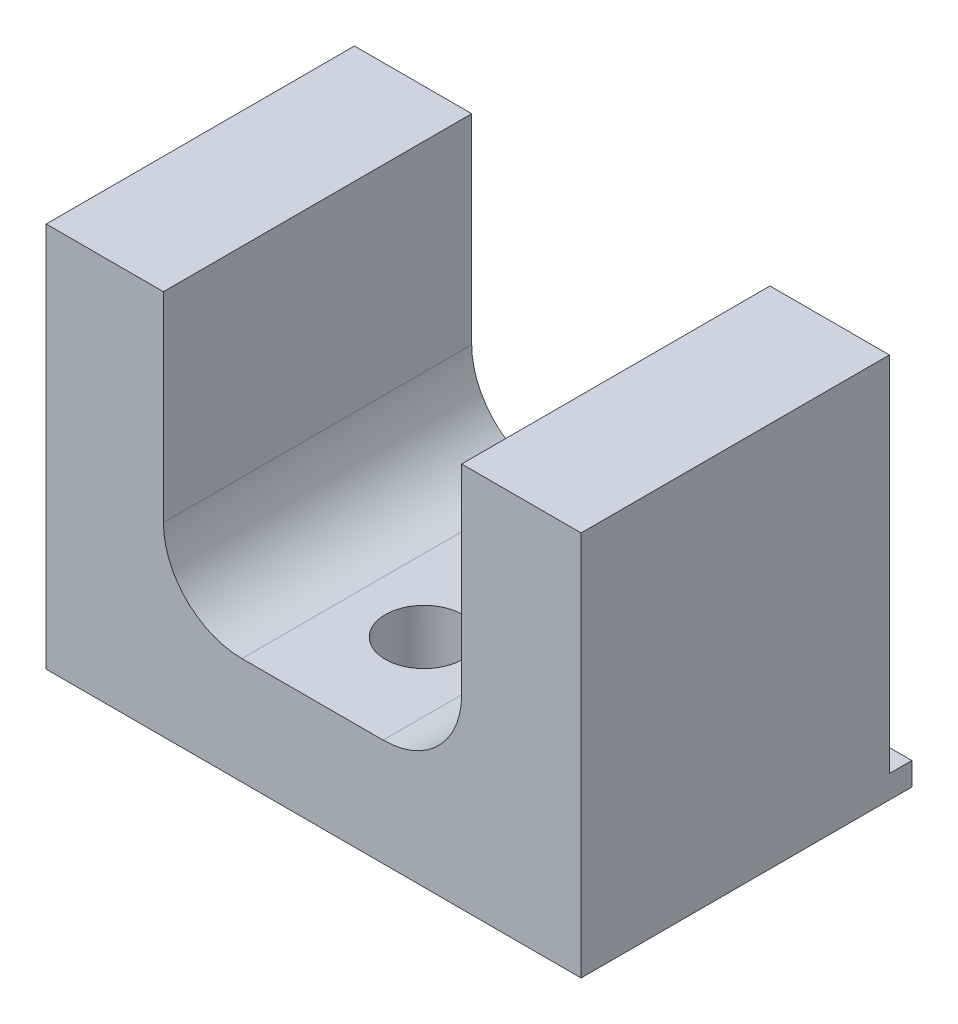
SolidWorks part; units mm, degrees
ref_plane "Front Plane" through (0, 0, 0) normal (0, 0, 1) x (1, 0, 0)
ref_plane "Top Plane" through (0, 0, 0) normal (0, 1, 0) x (1, 0, 0)
ref_plane "Right Plane" through (0, 0, 0) normal (1, 0, 0) x (0, 0, -1)
sketch "Sketch1" plane through (0, 0, 0) normal (0, 0, 1) x (1, 0, 0)
  line L0 (0, 0) -> (72.96, 0)
  line L8 (0, 0) -> (0, 52.58)
  line L9 (0, 52.58) -> (15.99, 52.58)
  line L10 (15.99, 52.58) -> (15.99, 25.31)
  line L11 (26.7, 14.6) -> (45.96, 14.6)
  line L12 (56.67, 25.31) -> (56.67, 52.57)
  line L13 (56.67, 52.57) -> (72.96, 52.57)
  line L14 (72.96, 52.57) -> (72.96, 0)
  arc A0 (45.96, 14.6) -> (56.67, 25.31) centre (45.96, 25.31) ccw
  arc A1 (15.99, 25.31) -> (26.7, 14.6) centre (26.7, 25.31) ccw
  dimension "D7" = 10.71
  dimension "D1" = 72.96
  dimension "D2" = 52.58
  dimension "D3" = 14.6
  dimension "D4" = 15.99
  dimension "D5" = 16.29
  dimension "D6" = 52.57
extrude "Boss-Extrude1" add sketch "Sketch1" against normal blind 45.11
sketch "Sketch2" plane through (72.96, 0, 0) normal (1, 0, 0) x (0, 0, -1)
  line L0 (45.11, 0) -> (0, 0) construction
  line L2 (45.11, 52.57) -> (45.11, 3.13)
  line L3 (45.11, 3.13) -> (42.05, 3.13)
  line L4 (42.05, 52.57) -> (42.05, 3.13)
  line L5 (42.05, 52.57) -> (42.05, 55.6771)
  line L6 (42.05, 55.6771) -> (45.11, 55.6771)
  line L7 (45.11, 55.6771) -> (45.11, 52.57)
  dimension "D1" = 3.13
  dimension "D2" = 3.06
extrude "Cut-Extrude2" cut sketch "Sketch2" against normal blind 100 contours L5 L6 L7 L2 L3 L4
sketch "Sketch3" plane through (0, 0, 0) normal (0, -1, 0) x (1, 0, 0)
  line L2 (0, 0) -> (72.96, 0) construction
  line L4 (72.96, -45.11) -> (72.96, 0) construction
  circle A0 centre (36.57, -14.97) radius 5.29
  dimension "D1" = 10.58
  dimension "D2" = 9.68
  dimension "D3" = 31.1
extrude "Cut-Extrude3" cut sketch "Sketch3" against normal blind 100
hole_wizard "M5x0.8 Tapped Hole1" positions "Sketch7" profile "Sketch9" tap size "M5x0.8" standard "ANSI Metric"
sketch "Sketch7" plane through (0, 0, -42.05) normal (0, 0, -1) x (-1, 0, 0)
  line L0 (-72.96, 3.13) -> (-72.96, 52.57) construction
  line L1 (-72.96, 52.57) -> (-56.67, 52.57) construction
  line L2 (0, 0) -> (-72.96, 0) construction
  line L3 (0, 52.58) -> (0, 3.13) construction
  line L4 (-10.06, 7.5) -> (-62.965, 7.5) construction
  line L5 (-62.965, 7.5) -> (-62.965, 42.405) construction
  line L6 (-62.965, 42.405) -> (-10.06, 42.405) construction
  line L7 (-10.06, 42.405) -> (-10.06, 7.5) construction
  point P0 (-62.965, 42.405)
  point P16 (-62.965, 7.5)
  point P18 (-10.06, 7.5)
  point P20 (-10.06, 42.405)
  dimension "D1" = 9.995
  dimension "D2" = 10.165
  dimension "D3" = 7.5
  dimension "D4" = 7.5
  dimension "D5" = 10.06
sketch "Sketch9" plane through (62.965, 42.405, -42.05) normal (1, 0, 0) x (0, 1, 0)
  line L0 (0, 0) -> (0, 29.1218)
  line L1 (0, 29.1218) -> (2.1, 27.86)
  line L2 (2.1, 27.86) -> (2.1, 0.425)
  line L3 (2.1, 0.425) -> (2.525, 0)
  line L5 (2.525, 0) -> (0, 0)
  line L6 (-2.1, 0.425) -> (-2.525, 0) construction
  line L10 (0, 29.1218) -> (-2.1, 27.86) construction
  line L11 (0, -6.35) -> (0, 107.95) construction
  dimension "Tap Drill Dia." = 4.2
  dimension "Tap Drill Depth" = 27.86
  dimension "Near C'Sink Dia." = 5.05
  dimension "Near C'Sink Angle" = 90
  dimension "Drill Angle" = 118
cosmetic thread "Hole Thread1" parameters "D1"=22.36, "D2"=5
cosmetic thread "Hole Thread8" parameters "D1"=22.36, "D2"=5
cosmetic thread "Hole Thread9" parameters "D1"=22.36, "D2"=5
cosmetic thread "Hole Thread10" parameters "D1"=22.36, "D2"=5
